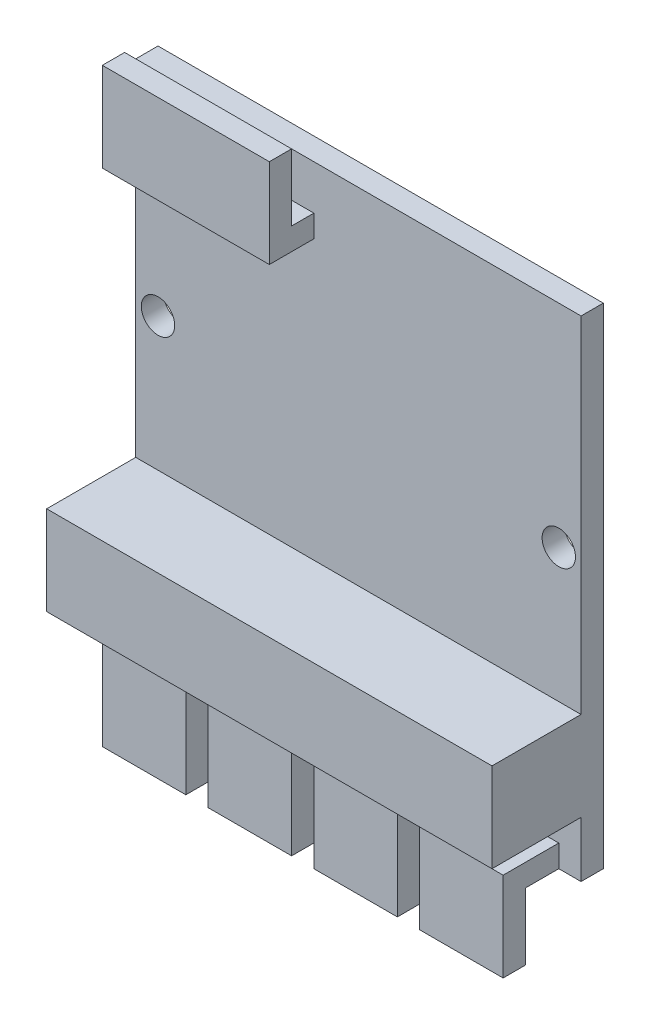
SolidWorks part; units mm, degrees
ref_plane "Plan de face" through (0, 0, 0) normal (0, 0, 1) x (1, 0, 0)
ref_plane "Plan de dessus" through (0, 0, 0) normal (0, 1, 0) x (1, 0, 0)
ref_plane "Plan de droite" through (0, 0, 0) normal (1, 0, 0) x (0, 0, -1)
sketch "Esquisse1" plane through (0, 0, 0) normal (0, 0, 1) x (1, 0, 0)
  line L1 (-20, -22) -> (20, -22)
  line L2 (-20, -22) -> (-20, 22)
  line L3 (-20, 22) -> (20, 22)
  line L4 (20, -22) -> (20, 22)
  line L5 (-20, -22) -> (20, 22) construction
  line L6 (-20, 22) -> (20, -22) construction
  point P0 (0, 0)
  dimension "D1" = 44
  dimension "D2" = 40
extrude "Boss.-Extru.1" add sketch "Esquisse1" along normal blind 2
sketch "Esquisse2" plane through (0, 0, 2) normal (0, 0, 1) x (1, 0, 0)
  line L0 (-20, 22) -> (-20, -22) construction
  line L1 (-20, -9) -> (20, -9)
  line L2 (-20, -9) -> (-20, -17)
  line L3 (-20, -17) -> (20, -17)
  line L4 (20, -9) -> (20, -17)
  line L5 (20, -22) -> (20, 22) construction
  line L6 (-20, -22) -> (20, -22) construction
  dimension "D1" = 5
  dimension "D2" = 8
extrude "Boss.-Extru.2" add sketch "Esquisse2" along normal blind 8 contours L1 L4 L3 L2
sketch "Esquisse3" plane through (0, 0, 2) normal (0, 0, 1) x (1, 0, 0)
  line L1 (-18, -22) -> (18, -22)
  line L2 (-18, -22) -> (-18, -20)
  line L3 (-18, -20) -> (18, -20)
  line L4 (18, -22) -> (18, -20)
  line L5 (-20, -22) -> (20, -22) construction
  point P6 (0, -22)
  dimension "D1" = 36
  dimension "D2" = 2
extrude "Boss.-Extru.3" add sketch "Esquisse3" along normal blind 5
sketch "Esquisse4" plane through (0, -22, 0) normal (0, -1, 0) x (1, 0, 0)
  line L0 (18, 7) -> (18, 2) construction
  line L1 (-18, 7) -> (18, 7)
  line L2 (-18, 7) -> (-18, 5)
  line L3 (-18, 5) -> (18, 5)
  line L4 (18, 7) -> (18, 5)
  dimension "D1" = 2
extrude "Boss.-Extru.4" add sketch "Esquisse4" along normal blind 6
sketch "Esquisse5" plane through (0, -28, 0) normal (0, -1, 0) x (1, 0, 0)
  line L0 (18, 7) -> (-18, 7) construction
  line L1 (-10.5, 7) -> (-8.5, 7)
  line L2 (-10.5, 7) -> (-10.5, 2)
  line L3 (-10.5, 2) -> (-8.5, 2)
  line L4 (-8.5, 7) -> (-8.5, 2)
  line L5 (-20, 2) -> (20, 2) construction
  line L6 (-1, 7) -> (1, 7)
  line L7 (-1, 7) -> (-1, 2)
  line L8 (-1, 2) -> (1, 2)
  line L9 (1, 7) -> (1, 2)
  line L10 (8.5, 7) -> (10.5, 7)
  line L11 (8.5, 7) -> (8.5, 2)
  line L12 (8.5, 2) -> (10.5, 2)
  line L13 (10.5, 7) -> (10.5, 2)
  point P18 (0, 2)
  dimension "D1" = 2
  dimension "D2" = 7.5
  dimension "D3" = 7.5
extrude "Enlèv. mat.-Extru.1" cut sketch "Esquisse5" against normal up to next
sketch "Esquisse6" plane through (0, 0, 2) normal (0, 0, 1) x (1, 0, 0)
  line L0 (20, 22) -> (-20, 22) construction
  line L1 (-19, 18) -> (-4, 18)
  line L2 (-19, 18) -> (-19, 16)
  line L3 (-19, 16) -> (-4, 16)
  line L4 (-4, 18) -> (-4, 16)
  line L5 (-20, 22) -> (-20, -9) construction
  dimension "D1" = 4
  dimension "D2" = 1
  dimension "D3" = 15
  dimension "D4" = 2
extrude "Boss.-Extru.5" add sketch "Esquisse6" along normal blind 4
sketch "Esquisse7" plane through (0, 18, 0) normal (0, 1, 0) x (1, 0, 0)
  line L0 (-4, -6) -> (-4, -2) construction
  line L1 (-19, -6) -> (-4, -6)
  line L2 (-19, -6) -> (-19, -4)
  line L3 (-19, -4) -> (-4, -4)
  line L4 (-4, -6) -> (-4, -4)
  dimension "D1" = 2
extrude "Boss.-Extru.6" add sketch "Esquisse7" along normal blind 6
sketch "Esquisse8" plane through (0, 0, 2) normal (0, 0, 1) x (1, 0, 0)
  line L0 (20, 22) -> (-20, 22) construction
  line L1 (20, -9) -> (20, 22) construction
  circle A0 centre (18, 3) radius 1.5
  dimension "D2" = 3
  dimension "D1" = 19
  dimension "D3" = 2
extrude "Enlèv. mat.-Extru.2" cut sketch "Esquisse8" against normal up to next contours A0
mirror "Symétrie1" about plane through (0, 0, 0) normal (1, 0, 0) of "Enlèv. mat.-Extru.2"
